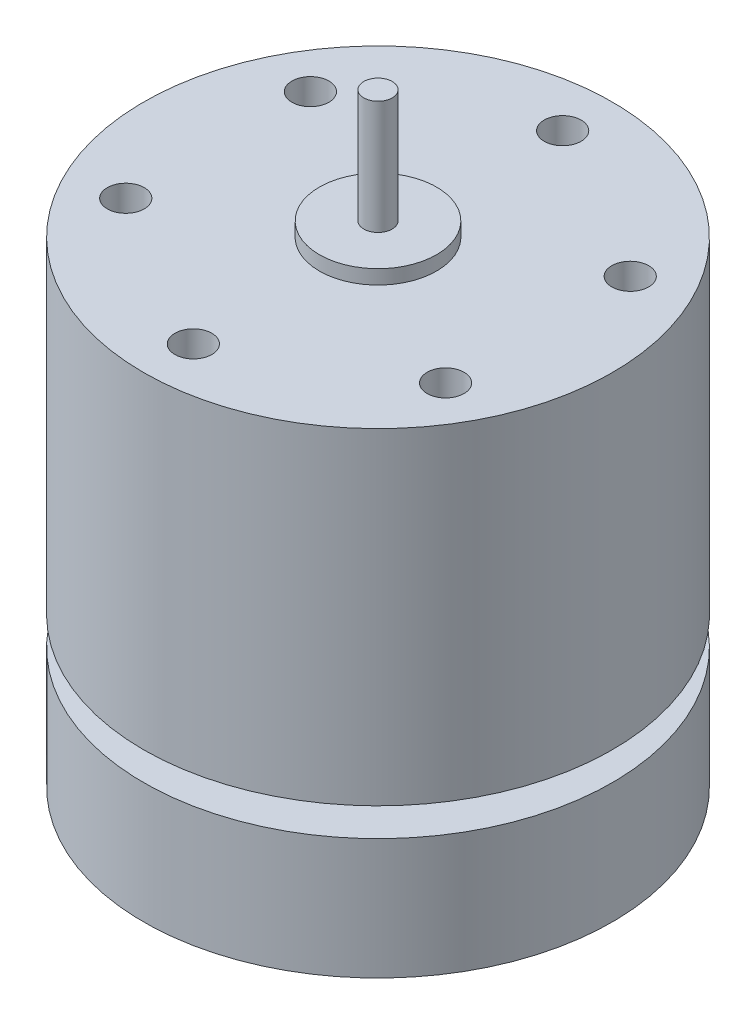
SolidWorks part; units mm, degrees
ref_plane "前视基准面" through (0, 0, 0) normal (0, 0, 1) x (1, 0, 0)
ref_plane "上视基准面" through (0, 0, 0) normal (0, 1, 0) x (1, 0, 0)
ref_plane "右视基准面" through (0, 0, 0) normal (1, 0, 0) x (0, 0, -1)
sketch "草图1" plane through (0, 0, 0) normal (0, 1, 0) x (1, 0, 0)
  circle A0 centre (0, 0) radius 16.5
extrude "凸台-拉伸1" add sketch "草图1" along normal blind 23
sketch "草图2" plane through (0, 23, 0) normal (0, 1, 0) x (1, 0, 0)
  circle A0 centre (0, 0) radius 4.125
extrude "凸台-拉伸2" add sketch "草图2" along normal blind 1
sketch "草图3" plane through (0, 24, 0) normal (0, 1, 0) x (1, 0, 0)
  circle A0 centre (0, 0) radius 1
extrude "凸台-拉伸3" add sketch "草图3" along normal blind 8
sketch "草图4" plane through (0, 0, 0) normal (0, -1, 0) x (1, 0, 0)
  circle A0 centre (0, 0) radius 3
extrude "凸台-拉伸4" add sketch "草图4" along normal blind 2
sketch "草图5" plane through (0, -2, 0) normal (0, -1, 0) x (-1, 0, 0)
  circle A0 centre (0, 0) radius 16.5
extrude "凸台-拉伸5" add sketch "草图5" along normal blind 8.5
sketch "草图6" plane through (0, 23, 0) normal (0, 1, 0) x (1, 0, 0)
  line L1 (1.1258, -12.35) -> (10.1325, -7.15)
  line L2 (11.2583, -5.2) -> (11.2583, 5.2)
  line L3 (10.1325, 7.15) -> (1.1258, 12.35)
  line L4 (-1.1258, 12.35) -> (-10.1325, 7.15)
  line L5 (-11.2583, 5.2) -> (-11.2583, -5.2)
  line L6 (-10.1325, -7.15) -> (-1.1258, -12.35)
  arc A0 (11.8512, -5.3431) -> (11.8512, 5.3431) centre (0, 0) ccw
  circle A1 centre (0, 0) radius 11.2583 construction
  circle A2 centre (0, -13) radius 1.3
  circle A3 centre (-11.2583, -6.5) radius 1.3
  circle A4 centre (-11.2583, 6.5) radius 1.3
  circle A5 centre (0, 13) radius 1.3
  circle A6 centre (11.2583, 6.5) radius 1.3
  circle A7 centre (11.2583, -6.5) radius 1.3
  arc A8 (1.2984, -12.935) -> (10.5529, -7.5919) centre (0, 0) ccw
  arc A9 (-10.5529, -7.5919) -> (-1.2984, -12.935) centre (0, 0) ccw
  arc A10 (-11.8512, 5.3431) -> (-11.8512, -5.3431) centre (0, 0) ccw
  arc A11 (-1.2984, 12.935) -> (-10.5529, 7.5919) centre (0, 0) ccw
  arc A12 (10.5529, 7.5919) -> (1.2984, 12.935) centre (0, 0) ccw
extrude "切除-拉伸1" cut sketch "草图6" against normal blind 2 contours A3 | A2 | A7 | A6 | A5 | A4
